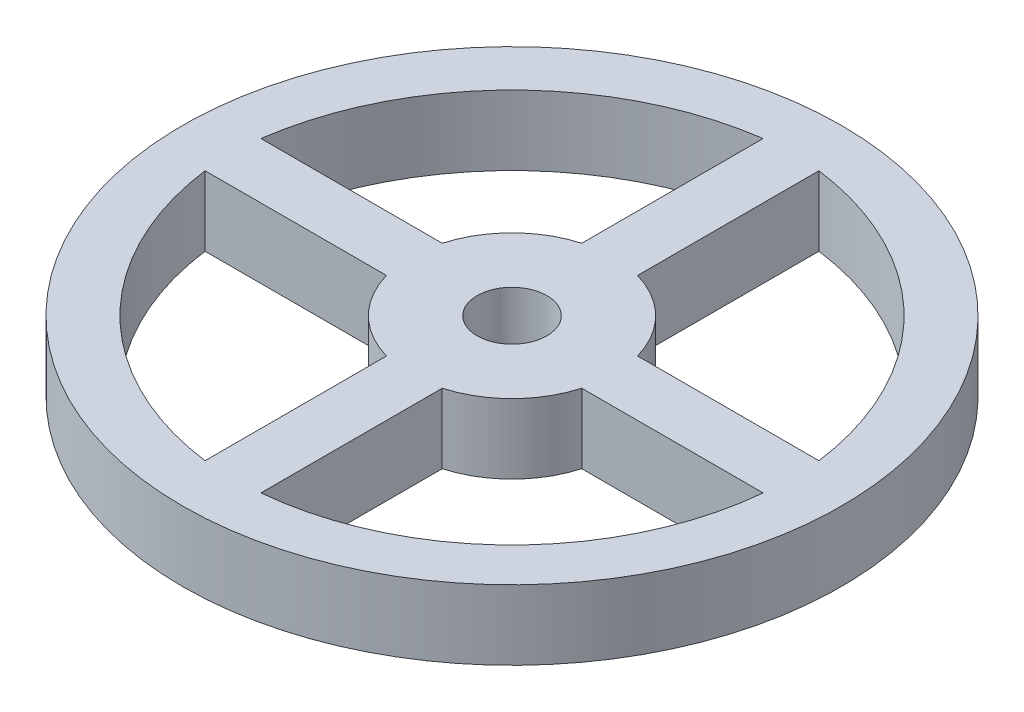
SolidWorks part; units mm, degrees
ref_plane "Front Plane" through (0, 0, 0) normal (0, 0, 1) x (1, 0, 0)
ref_plane "Top Plane" through (0, 0, 0) normal (0, 1, 0) x (1, 0, 0)
ref_plane "Right Plane" through (0, 0, 0) normal (1, 0, 0) x (0, 0, -1)
sketch "Sketch1" plane through (0, 0, 0) normal (0, 1, 0) x (1, 0, 0)
  circle A0 centre (0, 0) radius 30
  point P3 (0, 0)
  dimension "D1" = 60
extrude "Boss-Extrude1" add sketch "Sketch1" along normal blind 6.35
sketch "Sketch2" plane through (0, 6.35, 0) normal (0, 1, 0) x (1, 0, 0)
  circle A0 centre (0, 0) radius 3.175
  dimension "D1" = 6.35
extrude "Cut-Extrude1" cut sketch "Sketch2" against normal through all
sketch "Sketch3" plane through (0, 6.35, 0) normal (0, 1, 0) x (1, 0, 0)
  line L0 (0, -9.2457) -> (0, -25.4) construction
  line L1 (-9.2457, 0) -> (-25.4, 0) construction
  line L2 (0, 9.2457) -> (0, 25.4) construction
  line L3 (9.2457, 0) -> (25.4, 0) construction
  line L4 (8.89, -2.54) -> (25.4, -2.54)
  line L5 (-2.54, -8.89) -> (-2.54, -25.4)
  line L6 (-8.89, 2.54) -> (-25.4, 2.54)
  line L7 (2.54, 8.89) -> (2.54, 25.4)
  line L8 (8.89, 2.54) -> (25.4, 2.54)
  line L9 (2.54, -8.89) -> (2.54, -25.4)
  line L10 (-8.89, -2.54) -> (-25.4, -2.54)
  line L11 (-2.54, 8.89) -> (-2.54, 25.4)
  line L12 (9.2457, 2.54) -> (25.4, 2.54) construction
  line L13 (9.2457, -2.54) -> (25.4, -2.54) construction
  line L14 (2.54, -9.2457) -> (2.54, -25.4) construction
  line L15 (-2.54, -9.2457) -> (-2.54, -25.4) construction
  line L16 (-9.2457, -2.54) -> (-25.4, -2.54) construction
  line L17 (-9.2457, 2.54) -> (-25.4, 2.54) construction
  line L18 (-2.54, 9.2457) -> (-2.54, 25.4) construction
  line L19 (2.54, 9.2457) -> (2.54, 25.4) construction
  circle A0 centre (0, 0) radius 25.4 construction
  circle A1 centre (0, 0) radius 9.2457 construction
  arc A3 (-2.54, -25.4) -> (-25.4, -2.54) centre (0.9454, 0.9454) cw
  arc A4 (-25.4, 2.54) -> (-2.54, 25.4) centre (1.1994, -1.1994) cw
  arc A5 (2.54, 25.4) -> (25.4, 2.54) centre (-0.9454, -0.9454) cw
  arc A6 (-2.54, -8.89) -> (-8.89, -2.54) centre (0, 0) cw
  arc A7 (-8.89, 2.54) -> (-2.54, 8.89) centre (0, 0) cw
  arc A8 (2.54, 8.89) -> (8.89, 2.54) centre (0, 0) cw
  arc A9 (8.89, -2.54) -> (2.54, -8.89) centre (0, 0) cw
  arc A10 (2.54, -25.4) -> (25.4, -2.54) centre (0.1159, -0.1159) ccw
  point P28 (0, 0)
  point P39 (6.3733, -6.3733)
  point P41 (2.54, -9.8287)
  dimension "D4" = 50.8
  dimension "D3" = 8.89
  dimension "D1" = 2.54
  dimension "D2" = 2.54
extrude "Cut-Extrude2" cut sketch "Sketch3" against normal through all
